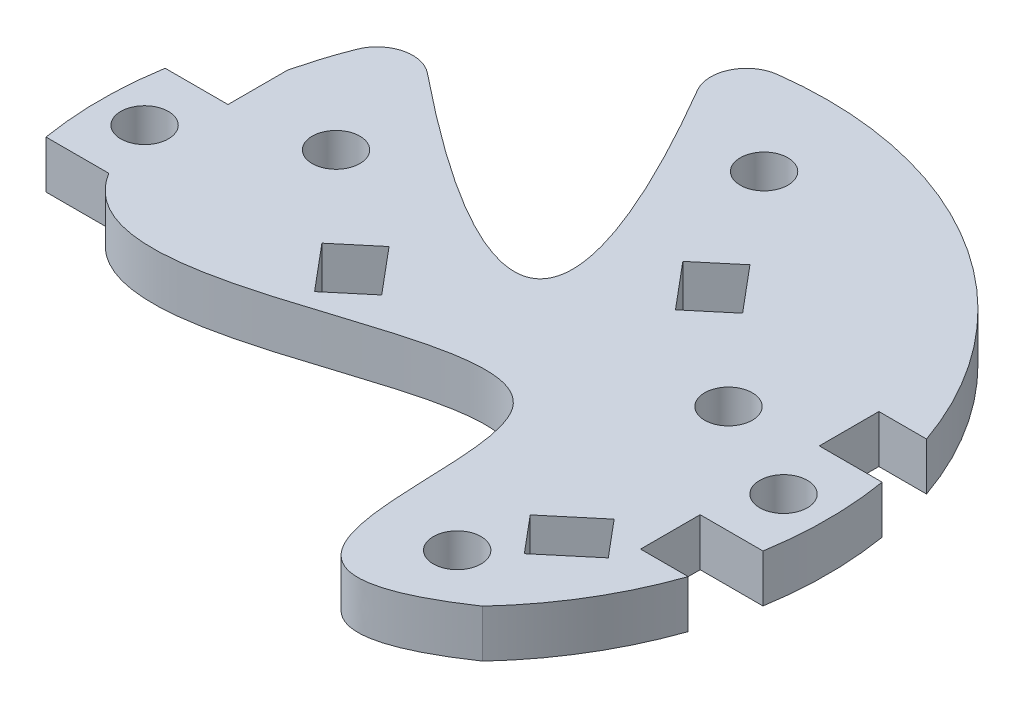
SolidWorks part; units mm, degrees
ref_plane "Alzado" through (0, 0, 0) normal (0, 0, 1) x (1, 0, 0)
ref_plane "Planta" through (0, 0, 0) normal (0, 1, 0) x (1, 0, 0)
ref_plane "Vista lateral" through (0, 0, 0) normal (1, 0, 0) x (0, 0, -1)
sketch "Croquis1" plane through (0, 0, 0) normal (0, 1, 0) x (1, 0, 0)
  circle A0 centre (0, 0) radius 30.5
extrude "Saliente-Extruir1" add sketch "Croquis1" along normal blind 4
sketch "Croquis5" plane through (0, 4, 0) normal (0, 1, 0) x (1, 0, 0)
  line L0 (0, 0) -> (0, 10)
  line L1 (28.8141, -5) -> (30.0874, -5)
  line L2 (28.8141, 5) -> (30.0874, 5)
  line L3 (-24.8141, 10) -> (-28.8141, 10)
  line L4 (24.8141, -5) -> (24.8141, -10)
  line L5 (-24.8141, -10) -> (-28.8141, -10)
  line L6 (24.8141, -5) -> (28.8141, -5)
  line L7 (24.8141, 5) -> (24.8141, 10)
  line L8 (-24.8141, 5) -> (-28.8141, 5)
  line L9 (-24.8141, 5) -> (-24.8141, 10)
  line L10 (-24.8141, -5) -> (-28.8141, -5)
  line L11 (-24.8141, -5) -> (-24.8141, -10)
  line L12 (24.8141, 5) -> (28.8141, 5)
  line L13 (24.8141, -10) -> (28.8141, -10)
  line L14 (24.8141, 10) -> (28.8141, 10)
  line L15 (-28.8141, 5) -> (-30.0874, 5)
  line L16 (-28.8141, -5) -> (-30.0874, -5)
  circle A1 centre (0, 0) radius 30.5 construction
  arc A2 (-28.8141, 10) -> (-30.0874, 5) centre (0, 0) ccw
  arc A3 (28.8141, 10) -> (28.8141, -10) centre (0, 0) cw
  arc A4 (-30.0874, -5) -> (-28.8141, -10) centre (0, 0) ccw
  arc A5 (30.0874, -5) -> (28.8141, -10) centre (0, 0) cw
  arc A6 (28.8141, 10) -> (30.0874, 5) centre (0, 0) cw
extrude "Cortar-Extruir3" cut sketch "Croquis5" against normal blind 4
sketch "Croquis9" plane through (0, 4, 0) normal (0, 1, 0) x (1, 0, 0)
  line L0 (7.2803, 10.7703) -> (22.8679, -7.8063)
  line L1 (-8.3073, 29.3469) -> (7.2803, 10.7703)
  line L2 (8.7375, 15.2565) -> (11.9514, 11.4263)
  line L3 (-24.8141, -5) -> (-24.8141, -10)
  line L4 (-24.8141, -10) -> (-28.8141, -10)
  line L6 (11.9514, 11.4263) -> (8.8872, 8.8552)
  line L7 (8.7375, 15.2565) -> (5.6733, 12.6854)
  line L9 (-10.7967, -1.1345) -> (-7.7325, 1.4366)
  line L10 (-7.5827, -4.9648) -> (-4.5186, -2.3936)
  line L11 (-10.7967, -1.1345) -> (-7.5827, -4.9648)
  line L13 (-24.8141, 10) -> (-28.8141, 10)
  line L19 (-7.5827, -4.9648) -> (-10.6469, -7.5359)
  line L20 (-7.7325, 1.4366) -> (-4.5186, -2.3936)
  line L21 (17.6971, -12.1451) -> (20.2682, -15.2093)
  line L22 (-4.5186, -2.3936) -> (-10.6469, -7.5359)
  line L23 (20.2682, -15.2093) -> (24.0984, -11.9954)
  line L24 (-10.6469, -7.5359) -> (-4.5186, -2.3936)
  line L25 (21.5273, -8.9312) -> (24.0984, -11.9954)
  line L26 (24.0984, -11.9954) -> (21.5273, -8.9312)
  line L27 (17.6971, -12.1451) -> (21.5273, -8.9312)
  circle A0 centre (2.5506, 22.6297) radius 2
  arc A1 (28.8141, 10) -> (-28.8141, 10) centre (0, 0) ccw construction
  circle A2 centre (18.1382, 4.0531) radius 2
  circle A4 centre (-16.9835, 6.2386) radius 2
  arc A5 (-28.8141, -10) -> (28.8141, -10) centre (0, 0) ccw construction
  arc A6 (-23.4189, 14.4323) -> (-18.7453, 15.6646) centre (-20.6289, 13.3296) cw
  arc A7 (-28.8141, -10) -> (22.3289, -20.7766) centre (0, 0) ccw
  arc A8 (-28.8141, 10) -> (-8.3073, 29.3469) centre (0, 0) cw
  circle A9 centre (17.204, -17.7804) radius 2
  spline S0 degree 3 poles (22.3289, -20.7766) (5.9738, -31.8512) (22.1768, 15.8352) (-18.2069, -15.8076) (-24.8141, -5) knots 0 0 0 0 0.44579 1 1 1 1
  spline S1 degree 3 poles (-24.8141, -5) (-26.3603, 1.5896) (-25.8363, 8.3159) (-23.4189, 14.4323) knots 0 0 0 0 0.831813 0.831813 0.831813 0.831813
  spline S2 degree 3 poles (-18.7453, 15.6646) (3.867, -2.5765) (8.0942, 2.4964) (-8.3073, 29.3469) knots 0.040528 0.040528 0.040528 0.040528 1 1 1 1
  dimension "D1" = 3
extrude "Cortar-Extruir6" cut sketch "Croquis9" against normal blind 10
fillet "Redondeo1" radius 3 1 edges at (-8.3073, 2, -29.3469)
sketch "Croquis10" plane through (0, 4, 0) normal (0, 1, 0) x (1, 0, 0)
  circle A0 centre (-26.8141, 0) radius 2
  circle A1 centre (26.8141, 0) radius 2
extrude "Cortar-Extruir7" cut sketch "Croquis10" against normal blind 4
